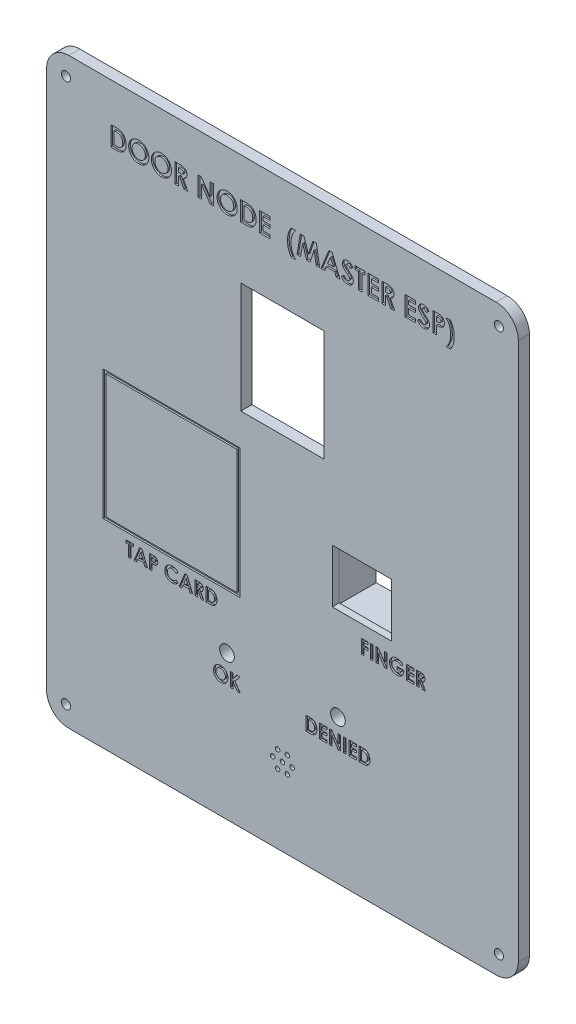
SolidWorks part; units mm, degrees
ref_plane "Front Plane" through (0, 0, 0) normal (0, 0, 1) x (1, 0, 0)
ref_plane "Top Plane" through (0, 0, 0) normal (0, 1, 0) x (1, 0, 0)
ref_plane "Right Plane" through (0, 0, 0) normal (1, 0, 0) x (0, 0, -1)
sketch "Sketch1" plane through (0, 0, 0) normal (0, 0, 1) x (1, 0, 0)
  line L0 (-77, 0) -> (77, 0)
  line L1 (85, 8) -> (85, 202)
  line L2 (77, 210) -> (-77, 210)
  line L3 (-85, 202) -> (-85, 8)
  arc A0 (-85, 8) -> (-77, 0) centre (-77, 8) ccw
  arc A1 (77, 0) -> (85, 8) centre (77, 8) ccw
  arc A2 (85, 202) -> (77, 210) centre (77, 202) ccw
  arc A3 (-77, 210) -> (-85, 202) centre (-77, 202) ccw
extrude "Panel" add sketch "Sketch1" along normal blind 4
ref_plane "P1_Front_4" through (0, 0, 4) normal (0, 0, 1) x (1, 0, 0)
sketch "Sketch2" plane through (0, 0, 0) normal (0, 0, 1) x (1, 0, 0)
  circle A0 centre (-78, 7) radius 1.65
  circle A1 centre (78, 7) radius 1.65
  circle A2 centre (-78, 203) radius 1.65
  circle A3 centre (78, 203) radius 1.65
extrude "Screw holes" cut sketch "Sketch2" along normal through all
ref_plane "P2_Front_-3" through (0, 0, -3) normal (0, 0, 1) x (1, 0, 0)
sketch "Sketch3" plane through (0, 0, -3) normal (0, 0, 1) x (1, 0, 0)
  line L1 (-15, 3.3) -> (15, 3.3)
  line L2 (-15, 3.3) -> (-15, 5.3)
  line L3 (-15, 5.3) -> (15, 5.3)
  line L4 (15, 3.3) -> (15, 5.3)
  line L6 (-15, 204.7) -> (15, 204.7)
  line L7 (-15, 204.7) -> (-15, 206.7)
  line L8 (-15, 206.7) -> (15, 206.7)
  line L9 (15, 204.7) -> (15, 206.7)
  line L11 (-81.7, 90) -> (-79.7, 90)
  line L12 (-81.7, 90) -> (-81.7, 120)
  line L13 (-81.7, 120) -> (-79.7, 120)
  line L14 (-79.7, 90) -> (-79.7, 120)
  line L16 (79.7, 90) -> (81.7, 90)
  line L17 (79.7, 90) -> (79.7, 120)
  line L18 (79.7, 120) -> (81.7, 120)
  line L19 (81.7, 90) -> (81.7, 120)
extrude "Locating tabs" add sketch "Sketch3" along normal blind 3
sketch "Sketch4" plane through (0, 0, 0) normal (0, 0, 1) x (1, 0, 0)
  line L1 (-15, 130) -> (15, 130)
  line L2 (-15, 130) -> (-15, 170)
  line L3 (-15, 170) -> (15, 170)
  line L4 (15, 130) -> (15, 170)
  line L5 (-15, 130) -> (15, 170) construction
  line L6 (-15, 170) -> (15, 130) construction
  point P0 (0, 150)
extrude "TFT window" cut sketch "Sketch4" along normal through all
ref_plane "P3_Front_-2.4" through (0, 0, -2.4) normal (0, 0, 1) x (1, 0, 0)
sketch "Sketch5" plane through (0, 0, -2.4) normal (0, 0, 1) x (1, 0, 0)
  circle A0 centre (-14.25, 124) radius 2.1
  circle A1 centre (-14.25, 176) radius 2.1
  circle A2 centre (14.25, 124) radius 2.1
  circle A3 centre (14.25, 176) radius 2.1
extrude "TFT bosses" add sketch "Sketch5" along normal blind 2.4
ref_plane "P4_Front_-2.4" through (0, 0, -2.4) normal (0, 0, 1) x (1, 0, 0)
sketch "Sketch6" plane through (0, 0, -2.4) normal (0, 0, 1) x (1, 0, 0)
  circle A0 centre (-14.25, 124) radius 1.1
  circle A1 centre (-14.25, 176) radius 1.1
  circle A2 centre (14.25, 124) radius 1.1
  circle A3 centre (14.25, 176) radius 1.1
extrude "TFT pilot holes" cut sketch "Sketch6" along normal blind 4
sketch "Sketch7" plane through (0, 0, 0) normal (0, 0, 1) x (1, 0, 0)
  line L1 (-61.65, 74.65) -> (-18.35, 74.65)
  line L2 (-61.65, 74.65) -> (-61.65, 115.35)
  line L3 (-61.65, 115.35) -> (-18.35, 115.35)
  line L4 (-18.35, 74.65) -> (-18.35, 115.35)
  line L5 (-61.65, 74.65) -> (-18.35, 115.35) construction
  line L6 (-61.65, 115.35) -> (-18.35, 74.65) construction
  circle A0 centre (-53.9, 82.4) radius 3
  circle A1 centre (-53.9, 107.6) radius 3
  circle A2 centre (-26.1, 82.4) radius 3
  circle A3 centre (-26.1, 107.6) radius 3
  point P0 (-40, 95)
extrude "NFC pocket" cut sketch "Sketch7" along normal blind 2.5
sketch "Sketch8" plane through (0, 0, 0) normal (0, 0, 1) x (1, 0, 0)
  circle A0 centre (-53.9, 82.4) radius 1.1
  circle A1 centre (-53.9, 107.6) radius 1.1
  circle A2 centre (-26.1, 82.4) radius 1.1
  circle A3 centre (-26.1, 107.6) radius 1.1
extrude "NFC pilot holes" cut sketch "Sketch8" along normal blind 3
sketch "Sketch9" plane through (0, 0, 4) normal (0, 0, 1) x (1, 0, 0)
  line L1 (-64.65, 71.65) -> (-15.35, 71.65)
  line L2 (-64.65, 71.65) -> (-64.65, 118.35)
  line L3 (-64.65, 118.35) -> (-15.35, 118.35)
  line L4 (-15.35, 71.65) -> (-15.35, 118.35)
  line L5 (-64.65, 71.65) -> (-15.35, 118.35) construction
  line L6 (-64.65, 118.35) -> (-15.35, 71.65) construction
  point P0 (-40, 95)
extrude "NFC tap outline recess" cut sketch "Sketch9" against normal blind 0.6
ref_plane "P5_Front_3.4" through (0, 0, 3.4) normal (0, 0, 1) x (1, 0, 0)
sketch "Sketch10" plane through (0, 0, 3.4) normal (0, 0, 1) x (1, 0, 0)
  line L1 (-63.65, 72.65) -> (-16.35, 72.65)
  line L2 (-63.65, 72.65) -> (-63.65, 117.35)
  line L3 (-63.65, 117.35) -> (-16.35, 117.35)
  line L4 (-16.35, 72.65) -> (-16.35, 117.35)
  line L5 (-63.65, 72.65) -> (-16.35, 117.35) construction
  line L6 (-63.65, 117.35) -> (-16.35, 72.65) construction
  point P0 (-40, 95)
extrude "NFC tap outline fill" add sketch "Sketch10" along normal blind 0.6
sketch "Sketch11" plane through (0, 0, 0) normal (0, 0, 1) x (1, 0, 0)
  line L1 (17.8, 84.85) -> (62.2, 84.85)
  line L2 (17.8, 84.85) -> (17.8, 105.15)
  line L3 (17.8, 105.15) -> (62.2, 105.15)
  line L4 (62.2, 84.85) -> (62.2, 105.15)
  line L5 (17.8, 84.85) -> (62.2, 105.15) construction
  line L6 (17.8, 105.15) -> (62.2, 84.85) construction
  point P0 (40, 95)
extrude "Fingerprint pocket" cut sketch "Sketch11" along normal blind 1.5
sketch "Sketch12" plane through (0, 0, 0) normal (0, 0, 1) x (1, 0, 0)
  line L1 (17.95, 85.35) -> (39.25, 85.35)
  line L2 (17.95, 85.35) -> (17.95, 104.65)
  line L3 (17.95, 104.65) -> (39.25, 104.65)
  line L4 (39.25, 85.35) -> (39.25, 104.65)
  line L5 (17.95, 85.35) -> (39.25, 104.65) construction
  line L6 (17.95, 104.65) -> (39.25, 85.35) construction
  point P0 (28.6, 95)
extrude "Fingerprint aperture" cut sketch "Sketch12" along normal through all
ref_plane "P6_Front_-12" through (0, 0, -12) normal (0, 0, 1) x (1, 0, 0)
sketch "Sketch13" plane through (0, 0, -12) normal (0, 0, 1) x (1, 0, 0)
  line L1 (15.8, 105.15) -> (62.2, 105.15)
  line L2 (15.8, 105.15) -> (15.8, 107.15)
  line L3 (15.8, 107.15) -> (62.2, 107.15)
  line L4 (62.2, 105.15) -> (62.2, 107.15)
  line L6 (15.8, 82.85) -> (62.2, 82.85)
  line L7 (15.8, 82.85) -> (15.8, 84.85)
  line L8 (15.8, 84.85) -> (62.2, 84.85)
  line L9 (62.2, 82.85) -> (62.2, 84.85)
extrude "Fingerprint cradle sides" add sketch "Sketch13" along normal blind 12
ref_plane "P7_Front_-12" through (0, 0, -12) normal (0, 0, 1) x (1, 0, 0)
sketch "Sketch14" plane through (0, 0, -12) normal (0, 0, 1) x (1, 0, 0)
  line L1 (15.8, 84.85) -> (17.8, 84.85)
  line L2 (15.8, 84.85) -> (15.8, 105.15)
  line L3 (15.8, 105.15) -> (17.8, 105.15)
  line L4 (17.8, 84.85) -> (17.8, 105.15)
extrude "Fingerprint cradle end" add sketch "Sketch14" along normal blind 12
ref_plane "P8_Top_108.15" through (0, 108.15, 0) normal (0, 1, 0) x (1, 0, 0)
sketch "Sketch15" plane through (0, 108.15, 0) normal (0, 1, 0) x (1, 0, 0)
  line L1 (28, 8) -> (32, 8)
  line L2 (28, 8) -> (28, 10.5)
  line L3 (28, 10.5) -> (32, 10.5)
  line L4 (32, 8) -> (32, 10.5)
  line L5 (28, 8) -> (32, 10.5) construction
  line L6 (28, 10.5) -> (32, 8) construction
  line L7 (48, 8) -> (52, 8)
  line L8 (48, 8) -> (48, 10.5)
  line L9 (48, 10.5) -> (52, 10.5)
  line L10 (52, 8) -> (52, 10.5)
  line L11 (48, 8) -> (52, 10.5) construction
  line L12 (48, 10.5) -> (52, 8) construction
  point P0 (30, 9.25)
  point P5 (50, 9.25)
extrude "Fingerprint tie slots" cut sketch "Sketch15" against normal through all
sketch "Sketch16" plane through (0, 0, 0) normal (0, 0, 1) x (1, 0, 0)
  circle A0 centre (-20, 52) radius 2.65
  circle A1 centre (20, 52) radius 2.65
extrude "LED holes" cut sketch "Sketch16" along normal through all
sketch "Sketch17" plane through (0, 0, 0) normal (0, 0, 1) x (1, 0, 0)
  circle A0 centre (0, 28) radius 0.8
  circle A1 centre (3.5, 28) radius 0.8
  circle A2 centre (1.75, 31.0311) radius 0.8
  circle A3 centre (-1.75, 31.0311) radius 0.8
  circle A4 centre (-3.5, 28) radius 0.8
  circle A5 centre (-1.75, 24.9689) radius 0.8
  circle A6 centre (1.75, 24.9689) radius 0.8
extrude "Buzzer sound holes" cut sketch "Sketch17" along normal through all
ref_plane "P9_Front_-7" through (0, 0, -7) normal (0, 0, 1) x (1, 0, 0)
sketch "Sketch18" plane through (0, 0, -7) normal (0, 0, 1) x (1, 0, 0)
  circle A0 centre (0, 28) radius 7.75
  circle A1 centre (0, 28) radius 6.15
extrude "Buzzer cradle" add sketch "Sketch18" along normal blind 7
sketch "Sketch19" plane through (0, 0, 4) normal (0, 0, 1) x (1, 0, 0)
  text T0 "DOOR NODE  (MASTER ESP)" font "Century Gothic" height 7
  text T1 "TAP CARD" font "Century Gothic" height 5
  text T2 "FINGER" font "Century Gothic" height 5
  text T3 "OK" font "Century Gothic" height 5
  text T4 "DENIED" font "Century Gothic" height 5
extrude "Labels (engraved)" cut sketch "Sketch19" against normal blind 0.6
